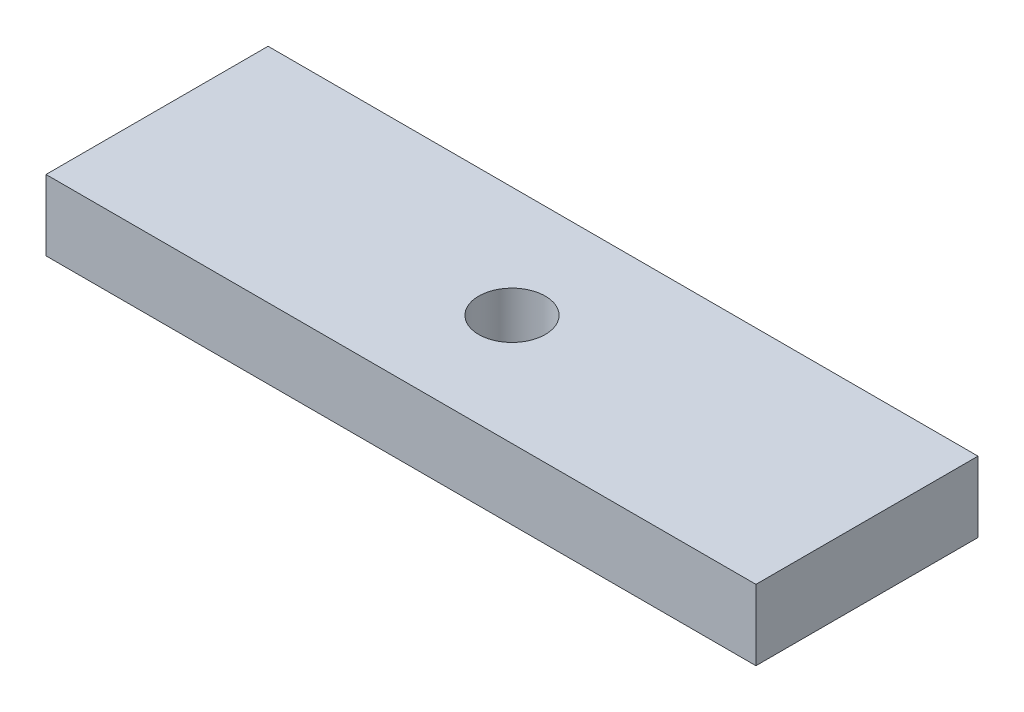
SolidWorks part; units mm, degrees
ref_plane "Front Plane" through (0, 0, 0) normal (0, 0, 1) x (1, 0, 0)
ref_plane "Top Plane" through (0, 0, 0) normal (0, 1, 0) x (1, 0, 0)
ref_plane "Right Plane" through (0, 0, 0) normal (1, 0, 0) x (0, 0, -1)
sketch "Sketch1" plane through (0, 0, 0) normal (0, 1, 0) x (1, 0, 0)
  line L1 (-31.97, 10) -> (31.97, 10)
  line L2 (-31.97, 10) -> (-31.97, -10)
  line L3 (-31.97, -10) -> (31.97, -10)
  line L4 (31.97, 10) -> (31.97, -10)
  line L5 (-31.97, 10) -> (31.97, -10) construction
  line L6 (-31.97, -10) -> (31.97, 10) construction
  circle A0 centre (0, 0) radius 3
  dimension "D1" = 6
  dimension "D2" = 20
  dimension "D3" = 63.94
extrude "Boss-Extrude1" add sketch "Sketch1" along normal blind 6.35
